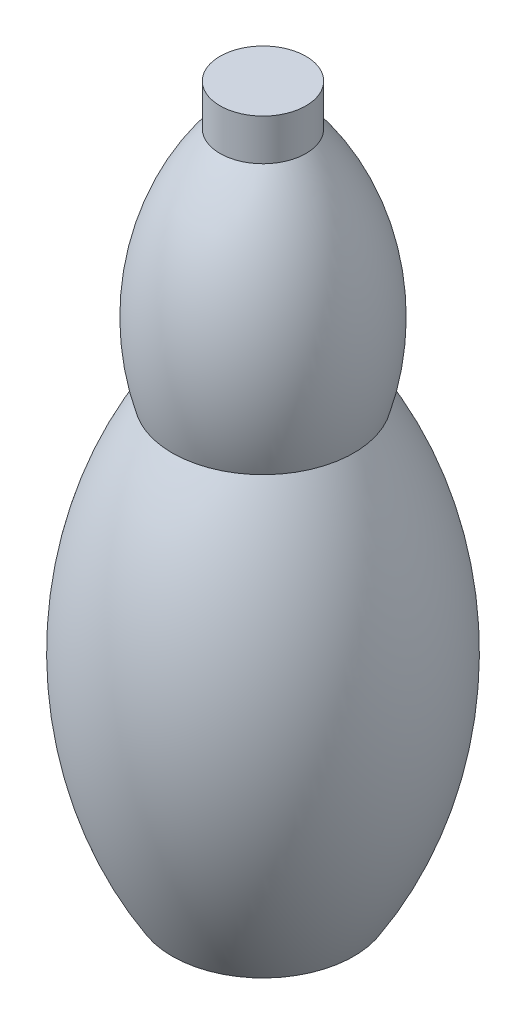
SolidWorks part; units mm, degrees
ref_plane "Alzado" through (0, 0, 0) normal (0, 0, 1) x (1, 0, 0)
ref_plane "Planta" through (0, 0, 0) normal (0, 1, 0) x (1, 0, 0)
ref_plane "Vista lateral" through (0, 0, 0) normal (1, 0, 0) x (0, 0, -1)
sketch "Croquis1" plane through (0, 0, 0) normal (0, 0, 1) x (1, 0, 0)
  line L0 (0, 0) -> (0, 150)
  line L1 (0, 150) -> (9.0421, 150)
  line L2 (9.0421, 150) -> (9.0421, 141.3053)
  line L3 (19.124, 0) -> (0, 0)
  arc A0 (9.0421, 141.3053) -> (19.124, 91.7541) centre (-32.8241, 106.9858) cw
  arc A1 (19.124, 91.7541) -> (19.124, 0) centre (-54.762, 45.8771) cw
  point P9 (0, 0)
  point P10 (6.3751, 111.5987)
  point P11 (0, 0)
  point P12 (0, 0)
  point P13 (-25.3244, 100.4392)
  point P14 (19.124, 91.7541)
  dimension "D1" = 150
revolve "Revolución1" add sketch "Croquis1" angle 360 about L0
